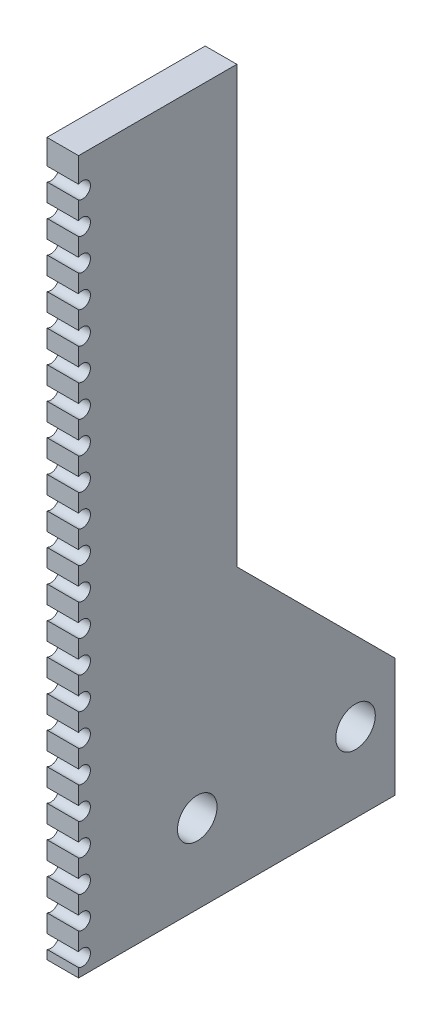
SolidWorks part; units mm, degrees
ref_plane "Спереди" through (0, 0, 0) normal (0, 0, 1) x (1, 0, 0)
ref_plane "Сверху" through (0, 0, 0) normal (0, 1, 0) x (1, 0, 0)
ref_plane "Справа" through (0, 0, 0) normal (1, 0, 0) x (0, 0, -1)
sketch "Эскиз1" plane through (0, 0, 0) normal (1, 0, 0) x (0, 0, -1)
  line L0 (40, 15) -> (20, 35)
  line L1 (0, 0) -> (40, 0)
  line L2 (0, 0) -> (0, 90)
  line L3 (0, 90) -> (20, 90)
  line L4 (40, 0) -> (40, 15)
  line L5 (20, 35) -> (20, 90)
  line L6 (0, 10) -> (40, 10) construction
  circle A0 centre (15, 10) radius 2.5
  circle A1 centre (35, 10) radius 2.5
  dimension "D7" = 5
  dimension "D1" = 40
  dimension "D2" = 90
  dimension "D3" = 20
  dimension "D4" = 15
  dimension "D5" = 20
  dimension "D6" = 10
  dimension "D8" = 20
  dimension "D9" = 5
extrude "Бобышка-Вытянуть1" add sketch "Эскиз1" along normal blind 4
sketch "Эскиз2" plane through (4, 0, 0) normal (1, 0, 0) x (0, 0, -1)
  line L0 (0.5, 90) -> (0.5, 0) construction
  line L1 (20, 90) -> (0, 90) construction
  line L2 (0, 0) -> (40, 0) construction
  line L3 (0, 90) -> (0, 0) construction
  line L4 (0.5, 94) -> (0.5, 4) construction
  line L5 (0.5, 98) -> (0.5, 8) construction
  line L6 (0.5, 102) -> (0.5, 12) construction
  line L7 (0.5, 106) -> (0.5, 16) construction
  line L8 (0.5, 110) -> (0.5, 20) construction
  line L9 (0.5, 114) -> (0.5, 24) construction
  line L10 (0.5, 118) -> (0.5, 28) construction
  line L11 (0.5, 122) -> (0.5, 32) construction
  line L12 (0.5, 126) -> (0.5, 36) construction
  line L13 (0.5, 130) -> (0.5, 40) construction
  line L14 (0.5, 134) -> (0.5, 44) construction
  line L15 (0.5, 138) -> (0.5, 48) construction
  line L16 (0.5, 142) -> (0.5, 52) construction
  line L17 (0.5, 146) -> (0.5, 56) construction
  line L18 (0.5, 150) -> (0.5, 60) construction
  line L19 (0.5, 154) -> (0.5, 64) construction
  line L20 (0.5, 158) -> (0.5, 68) construction
  line L21 (0.5, 162) -> (0.5, 72) construction
  line L22 (0.5, 166) -> (0.5, 76) construction
  line L23 (0.5, 170) -> (0.5, 80) construction
  line L24 (0.5, 174) -> (0.5, 84) construction
  circle A0 centre (0.5, 2) radius 1
  circle A1 centre (0.5, 6) radius 1
  circle A2 centre (0.5, 10) radius 1
  circle A3 centre (0.5, 14) radius 1
  circle A4 centre (0.5, 18) radius 1
  circle A5 centre (0.5, 22) radius 1
  circle A6 centre (0.5, 26) radius 1
  circle A7 centre (0.5, 30) radius 1
  circle A8 centre (0.5, 34) radius 1
  circle A9 centre (0.5, 38) radius 1
  circle A10 centre (0.5, 42) radius 1
  circle A11 centre (0.5, 46) radius 1
  circle A12 centre (0.5, 50) radius 1
  circle A13 centre (0.5, 54) radius 1
  circle A14 centre (0.5, 58) radius 1
  circle A15 centre (0.5, 62) radius 1
  circle A16 centre (0.5, 66) radius 1
  circle A17 centre (0.5, 70) radius 1
  circle A18 centre (0.5, 74) radius 1
  circle A19 centre (0.5, 78) radius 1
  circle A20 centre (0.5, 82) radius 1
  circle A21 centre (0.5, 86) radius 1
  dimension "D2" = 2
  dimension "D1" = 0.5
  dimension "D3" = 2
  dimension "D4" = 22
extrude "Вырез-Вытянуть1" cut sketch "Эскиз2" against normal blind 10
